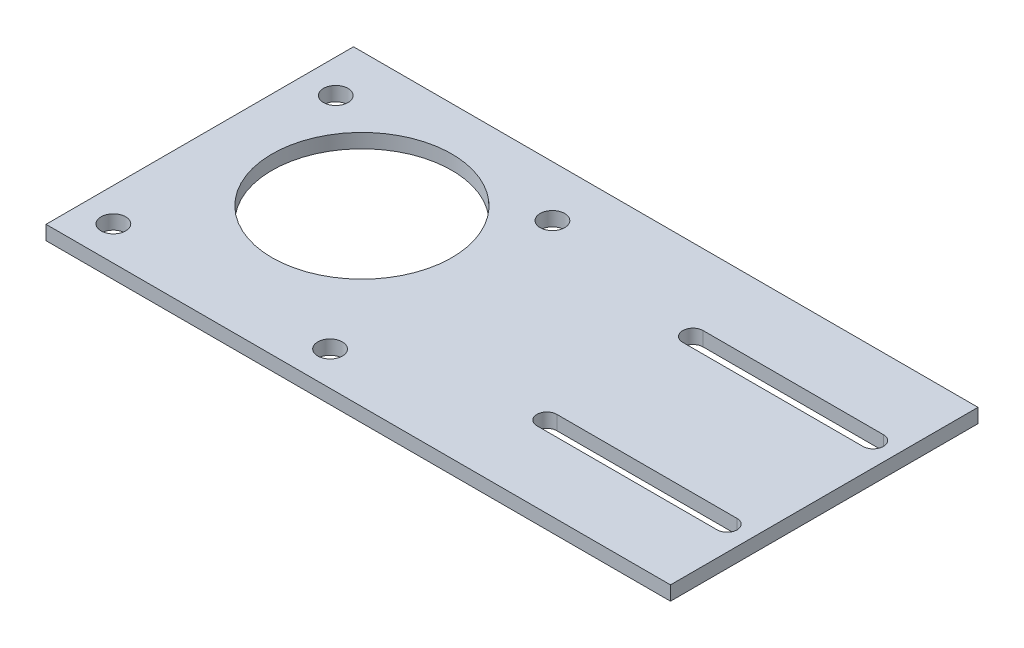
SolidWorks part; units mm, degrees
ref_plane "Front Plane" through (0, 0, 0) normal (0, 0, 1) x (1, 0, 0)
ref_plane "Top Plane" through (0, 0, 0) normal (0, 1, 0) x (1, 0, 0)
ref_plane "Right Plane" through (0, 0, 0) normal (1, 0, 0) x (0, 0, -1)
sketch "Sketch1" plane through (0, 0, 0) normal (0, 1, 0) x (1, 0, 0)
  line L1 (-38.1136, 24.6705) -> (93.8864, 24.6705)
  line L2 (-38.1136, 24.6705) -> (-38.1136, -40.3295)
  line L3 (-38.1136, -40.3295) -> (93.8864, -40.3295)
  line L4 (93.8864, 24.6705) -> (93.8864, -40.3295)
  dimension "D1" = 65
  dimension "D2" = 132
extrude "Boss-Extrude1" add sketch "Sketch1" along normal blind 3
sketch "Sketch2" plane through (0, 3, 0) normal (0, 1, 0) x (1, 0, 0)
  line L0 (-38.1136, 24.6705) -> (-38.1136, -40.3295) construction
  line L2 (-38.1136, -40.3295) -> (93.8864, -40.3295) construction
  circle A0 centre (-8.1136, -3.555) radius 19
  circle A1 centre (-31.0765, 13.8769) radius 2.6
  circle A2 centre (-31.0765, -33.1231) radius 2.6
  circle A3 centre (14.7257, 13.8769) radius 2.6
  circle A4 centre (14.7257, -33.1231) radius 2.6
  dimension "D1" = 38
  dimension "D4" = 47
  dimension "D5" = 5.2
  dimension "D6" = 36.7745
  dimension "D2" = 30
  dimension "D3" = 47
extrude "Cut-Extrude3" cut sketch "Sketch2" against normal blind 3
sketch "Sketch5" plane through (0, 3, 0) normal (0, 1, 0) x (1, 0, 0)
  line L0 (50.7938, 7.5115) -> (88.8938, 7.5115) construction
  line L1 (50.7938, 9.6705) -> (88.8938, 9.6705)
  line L2 (50.7938, 5.3525) -> (88.8938, 5.3525)
  line L3 (50.6585, -23.2295) -> (88.7585, -23.2295) construction
  line L4 (50.6585, -21.1295) -> (88.7585, -21.1295)
  line L5 (50.6585, -25.3295) -> (88.7585, -25.3295)
  line L6 (-38.1136, -40.3295) -> (93.8864, -40.3295) construction
  line L7 (93.8864, 24.6705) -> (-38.1136, 24.6705) construction
  arc A0 (50.7938, 9.6705) -> (50.7938, 5.3525) centre (50.7938, 7.5115) ccw
  arc A1 (88.8938, 5.3525) -> (88.8938, 9.6705) centre (88.8938, 7.5115) ccw
  arc A2 (50.6585, -21.1295) -> (50.6585, -25.3295) centre (50.6585, -23.2295) ccw
  arc A3 (88.7585, -25.3295) -> (88.7585, -21.1295) centre (88.7585, -23.2295) ccw
  circle A4 centre (-8.1136, -3.555) radius 19 construction
  point P2 (69.8438, 7.5115)
  point P7 (69.7085, -23.2295)
  dimension "D5" = 28.2255
  dimension "D1" = 38.1
  dimension "D2" = 38.1
  dimension "D3" = 4.2
  dimension "D4" = 4.318
  dimension "D6" = 15
  dimension "D7" = 15
extrude "Cut-Extrude5" cut sketch "Sketch5" against normal blind 3
